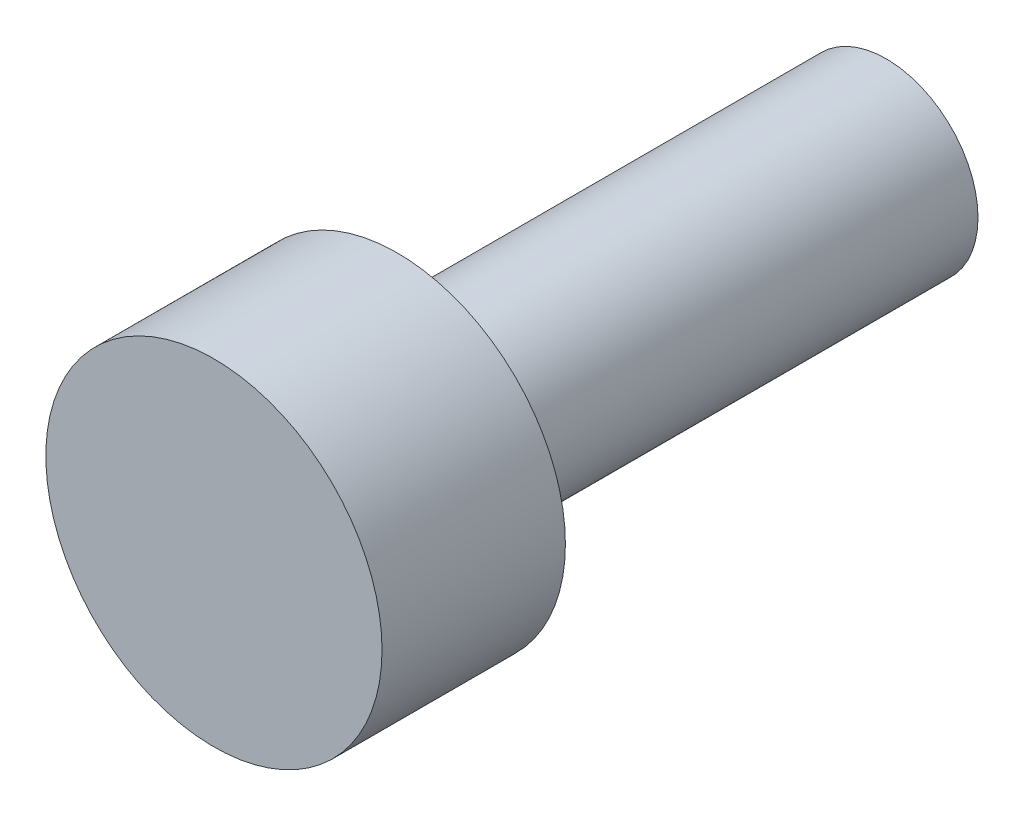
SolidWorks part; units mm, degrees
ref_plane "前视基准面" through (0, 0, 0) normal (0, 0, 1) x (1, 0, 0)
ref_plane "上视基准面" through (0, 0, 0) normal (0, 1, 0) x (1, 0, 0)
ref_plane "右视基准面" through (0, 0, 0) normal (1, 0, 0) x (0, 0, -1)
other "Configuration Table"
sketch "草图1" plane through (0, 0, 0) normal (0, 0, 1) x (1, 0, 0)
  circle A0 centre (0, 0) radius 1.5
extrude "M3杆" add sketch "草图1" along normal blind 8
sketch "草图2" plane through (0, 0, 0) normal (0, 0, 1) x (1, 0, 0)
  circle A0 centre (0, 0) radius 2.75
extrude "螺钉头" add sketch "草图2" along normal blind 3 from offset 8
